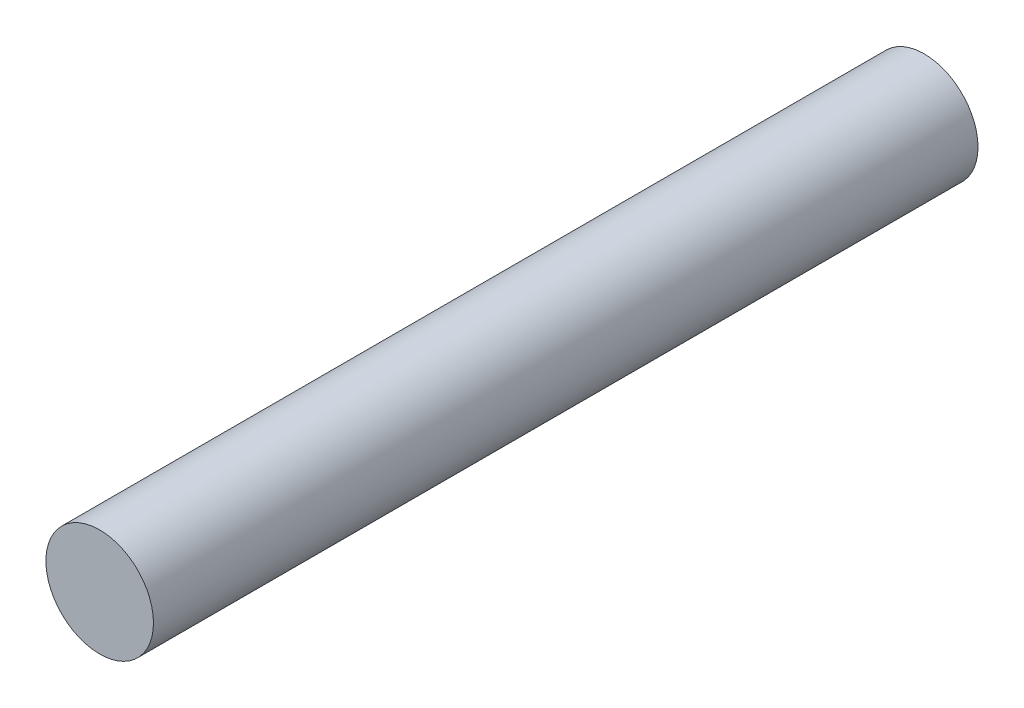
SolidWorks part; units mm, degrees
material "Aleación 1060"
ref_plane "Alzado" through (0, 0, 0) normal (0, 0, 1) x (1, 0, 0)
ref_plane "Planta" through (0, 0, 0) normal (0, 1, 0) x (1, 0, 0)
ref_plane "Vista lateral" through (0, 0, 0) normal (1, 0, 0) x (0, 0, -1)
sketch "Croquis1" plane through (0, 0, 0) normal (0, 0, 1) x (1, 0, 0)
  circle A0 centre (0, 0) radius 6
  dimension "D1" = 12
extrude "Saliente-Extruir1" add sketch "Croquis1" along normal blind 92
